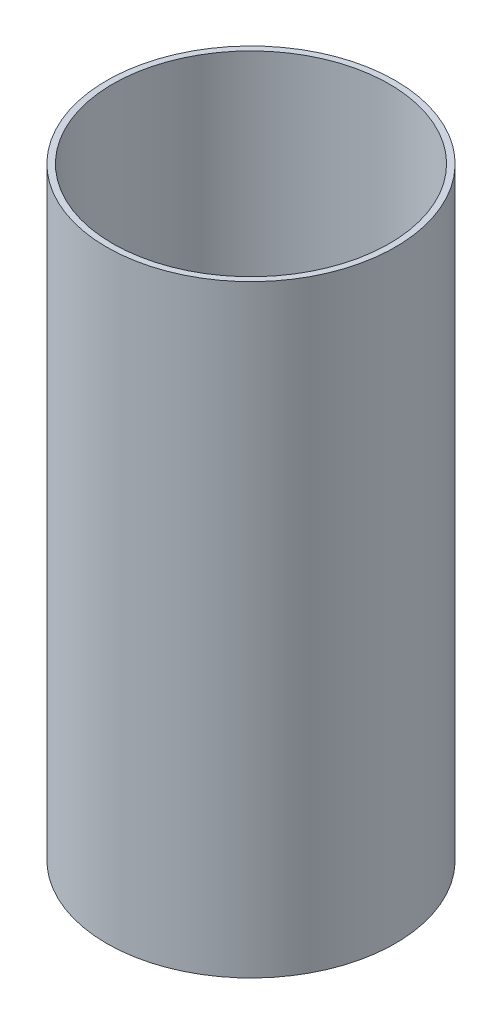
SolidWorks part; units mm, degrees
ref_plane "Front Plane" through (0, 0, 0) normal (0, 0, 1) x (1, 0, 0)
ref_plane "Top Plane" through (0, 0, 0) normal (0, 1, 0) x (1, 0, 0)
ref_plane "Right Plane" through (0, 0, 0) normal (1, 0, 0) x (0, 0, -1)
sketch "Sketch1" plane through (0, 0, 0) normal (0, 1, 0) x (1, 0, 0)
  circle A0 centre (-16.5477, 0) radius 34.4
  circle A1 centre (-16.5477, 0) radius 35.9
  dimension "D1" = 71.8
  dimension "D2" = 68.8
extrude "Boss-Extrude1" add sketch "Sketch1" along normal blind 150
